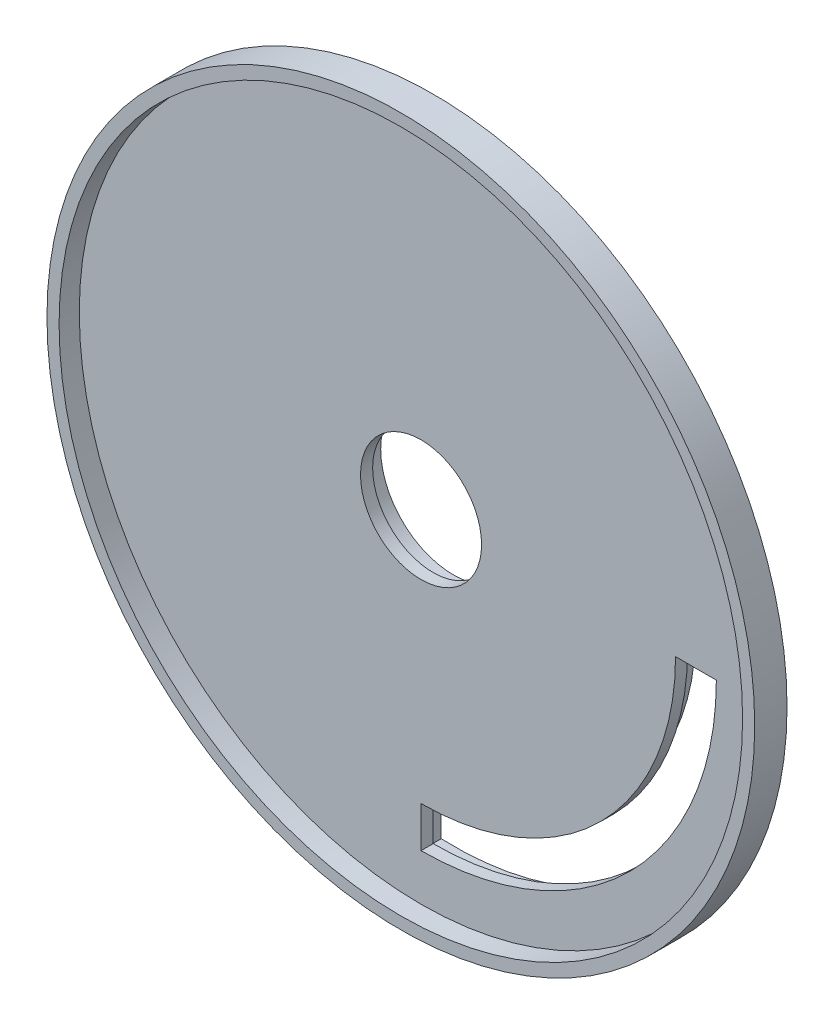
SolidWorks part; units mm, degrees
ref_plane "정면" through (0, 0, 0) normal (0, 0, 1) x (1, 0, 0)
ref_plane "윗면" through (0, 0, 0) normal (0, 1, 0) x (1, 0, 0)
ref_plane "우측면" through (0, 0, 0) normal (1, 0, 0) x (0, 0, -1)
sketch "스케치1" plane through (0, 0, 0) normal (0, 0, 1) x (1, 0, 0)
  circle A0 centre (0, 0) radius 87.6
  dimension "D1" = 175.2
extrude "보스-돌출1" add sketch "스케치1" along normal blind 3
sketch "스케치3" plane through (0, 0, 3) normal (0, 0, 1) x (1, 0, 0)
  circle A0 centre (0, 0) radius 84.6
  circle A1 centre (0, 0) radius 87.6
  circle A2 centre (0, 0) radius 87.6
  dimension "D2" = 169.2
  dimension "D1" = 0
extrude "보스-돌출2" add sketch "스케치3" along normal blind 5
sketch "스케치4" plane through (0, 0, 0) normal (0, 0, -1) x (-1, 0, 0)
  line L0 (-59.925, 3) -> (-76.0408, 3)
  line L1 (3, -76.0408) -> (3, -59.925)
  line L2 (-63, 0) -> (-73.1, 0)
  line L3 (0, -73.1) -> (0, -63)
  arc A0 (-59.925, 3) -> (3, -59.925) centre (0, 0) ccw
  arc A1 (-76.0408, 3) -> (3, -76.0408) centre (0, 0) ccw
  arc A2 (-73.1, 0) -> (0, -73.1) centre (0, 0) ccw
  arc A3 (-63, 0) -> (0, -63) centre (0, 0) ccw
  dimension "D1" = 60
  dimension "D2" = 76.1
  dimension "D3" = 16.1159
  dimension "D4" = 16.1159
  dimension "D5" = 3
extrude "컷-돌출1" cut sketch "스케치4" against normal blind 5 contours L2 A2 L3 A3
sketch "스케치5" plane through (0, 0, 0) normal (0, 0, -1) x (-1, 0, 0)
  line L0 (-59.925, 3) -> (-76.0408, 3)
  line L1 (3, -76.0408) -> (3, -59.925)
  line L4 (6, -78.8721) -> (6, -56.6833)
  line L5 (-56.6833, 6) -> (-78.8721, 6)
  arc A0 (-59.925, 3) -> (3, -59.925) centre (0, 0) ccw
  arc A1 (-76.0408, 3) -> (3, -76.0408) centre (0, 0) ccw
  arc A4 (-56.6833, 6) -> (6, -56.6833) centre (0, 0) ccw
  arc A5 (-78.8721, 6) -> (6, -78.8721) centre (0, 0) ccw
  dimension "D1" = 60
  dimension "D2" = 76.1
  dimension "D3" = 16.1159
  dimension "D4" = 16.1159
  dimension "D5" = 3
extrude "보스-돌출3" add sketch "스케치5" along normal blind 5
sketch "스케치6" plane through (0, 0, 0) normal (0, 0, -1) x (-1, 0, 0)
  circle A0 centre (0, 0) radius 17.9826
  circle A1 centre (0, 0) radius 14.9826
  dimension "D1" = 35.9652
  dimension "D2" = 29.9652
extrude "컷-돌출2" cut sketch "스케치6" against normal blind 5 contours A1
sketch "스케치7" plane through (0, 0, 0) normal (0, 0, -1) x (-1, 0, 0)
  circle A0 centre (0, 0) radius 17.9826
  circle A1 centre (0, 0) radius 14.9826
  circle A2 centre (0, 0) radius 20.9826
  dimension "D1" = 35.9652
  dimension "D2" = 29.9652
  dimension "D3" = 3
extrude "보스-돌출4" add sketch "스케치7" along normal blind 5 contours A2 A0
sketch "스케치12" plane through (0, 0, 0) normal (0, 1, 0) x (1, 0, 0)
  line L0 (83.7345, -3) -> (76.026, -3)
  line L1 (-84.6, -3) -> (84.6, -3) construction
